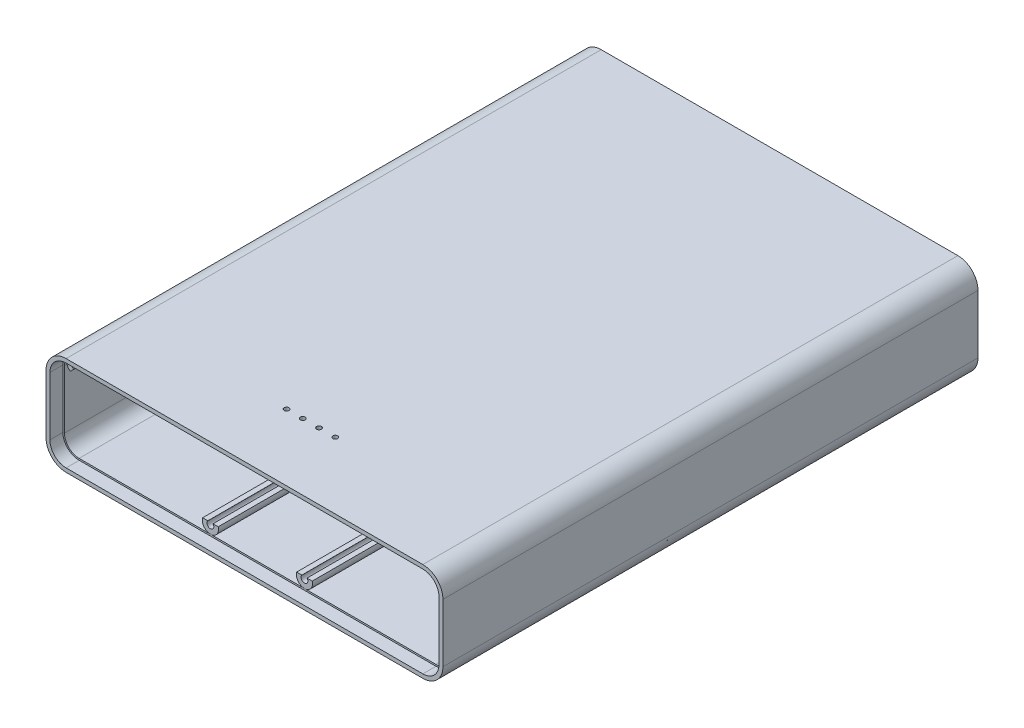
SolidWorks part; units mm, degrees
ref_plane "Front Plane" through (0, 0, 0) normal (0, 0, 1) x (1, 0, 0)
ref_plane "Top Plane" through (0, 0, 0) normal (0, 1, 0) x (1, 0, 0)
ref_plane "Right Plane" through (0, 0, 0) normal (1, 0, 0) x (0, 0, -1)
sketch "Sketch1" plane through (0, 0, 0) normal (0, 0, 1) x (1, 0, 0)
  line L0 (0, 0) -> (0, 26.7771) construction
  line L1 (0, 26.7771) -> (0, -20.8821) construction
  line L2 (0, 14) -> (55, 14)
  line L3 (0, 14) -> (-55, 14)
  line L4 (0, 0) -> (70.3724, 0) construction
  line L5 (73.8857, 0) -> (-73.8857, 0) construction
  line L6 (0, -14) -> (55, -14)
  line L7 (0, -14) -> (-55, -14)
  line L8 (-60, 9) -> (-60, -9)
  line L9 (60, 9) -> (60, -9)
  line L10 (0, 15.2) -> (-55, 15.2)
  line L11 (-61.2, 9) -> (-61.2, -9)
  line L12 (0, -15.2) -> (-55, -15.2)
  line L13 (0, -15.2) -> (55, -15.2)
  line L14 (61.2, 9) -> (61.2, -9)
  line L15 (0, 15.2) -> (55, 15.2)
  line L16 (0, 15.2) -> (-55, 15.2)
  line L17 (-61.2, 9) -> (-61.2, -9)
  line L18 (0, -15.2) -> (-55, -15.2)
  line L19 (0, -15.2) -> (55, -15.2)
  line L20 (61.2, 9) -> (61.2, -9)
  line L21 (0, 15.2) -> (55, 15.2)
  line L22 (-59.5, 9) -> (-59.5, -9)
  line L23 (0, -13.5) -> (-55, -13.5)
  line L24 (0, -13.5) -> (55, -13.5)
  line L25 (59.5, 9) -> (59.5, -9)
  line L26 (0, 13.5) -> (55, 13.5)
  line L27 (0, 13.5) -> (-55, 13.5)
  line L28 (53.8591, 10.8893) -> (57.1976, 8.1517)
  line L29 (-53.8591, 10.8893) -> (-57.1976, 8.1517)
  line L30 (16.7913, -10) -> (12.2087, -10)
  line L31 (-12.2087, -10) -> (-16.7913, -10)
  arc A0 (-55, 15.2) -> (-61.2, 9) centre (-55, 9) ccw
  arc A1 (-55, -15.2) -> (-61.2, -9) centre (-55, -9) cw
  arc A2 (55, -15.2) -> (61.2, -9) centre (55, -9) ccw
  arc A3 (55, 15.2) -> (61.2, 9) centre (55, 9) cw
  arc A4 (-55, 15.2) -> (-61.2, 9) centre (-55, 9) ccw
  arc A5 (-55, -15.2) -> (-61.2, -9) centre (-55, -9) cw
  arc A6 (55, -15.2) -> (61.2, -9) centre (55, -9) ccw
  arc A7 (55, 15.2) -> (61.2, 9) centre (55, 9) cw
  arc A8 (-55, 13.5) -> (-59.5, 9) centre (-55, 9) ccw
  arc A9 (-55, -13.5) -> (-59.5, -9) centre (-55, -9) cw
  arc A10 (55, -13.5) -> (59.5, -9) centre (55, -9) ccw
  arc A11 (55, 13.5) -> (59.5, 9) centre (55, 9) cw
  arc A12 (-53.8591, 10.8893) -> (-57.1976, 8.1517) centre (-56.3279, 10.4955) ccw
  arc A13 (-16.7913, -10) -> (-12.2087, -10) centre (-14.5, -11) ccw
  arc A14 (53.8591, 10.8893) -> (57.1976, 8.1517) centre (56.3279, 10.4955) cw
  arc A15 (16.7913, -10) -> (12.2087, -10) centre (14.5, -11) cw
  arc A16 (55, 14) -> (60, 9) centre (55, 9) cw
  arc A17 (55, -14) -> (60, -9) centre (55, -9) ccw
  arc A18 (-55, -14) -> (-60, -9) centre (-55, -9) cw
  arc A19 (-55, 14) -> (-60, 9) centre (-55, 9) ccw
  point P51 (60, 14)
  point P54 (60, -14)
  point P57 (-60, -14)
  point P60 (-60, 14)
  dimension "D2" = 1.2
  dimension "D3" = 1.2
  dimension "D10" = 0.5
  dimension "D11" = 5
  dimension "D12" = 45
  dimension "D13" = 2.5
  dimension "D14" = 2.5
  dimension "D15" = 2.5
  dimension "D4" = 28
  dimension "D5" = 60
  dimension "D6" = 60
  dimension "D7" = 60
  dimension "D8" = 60
  dimension "D9" = 28
  dimension "D16" = 3.5
  dimension "D17" = 1.2
  dimension "D18" = 0.5
extrude "Boss-Extrude2" add sketch "Sketch1" along normal blind 83 and the other way blind 82 contours A3 L15 L10 A0 L11 A1 L12 L13 A2 L14 A19 L3 L2 A16 L9 A17 L6 L7 A18 L8
sketch "Sketch2" plane through (0, 0, 0) normal (0, 0, 1) x (1, 0, 0)
  line L0 (0, 0.0525) -> (0, 26.8296) construction
  line L1 (0, 26.8296) -> (0, -20.8296) construction
  line L2 (0, 14.0525) -> (55, 14.0525)
  line L3 (0, 14.0525) -> (-55, 14.0525)
  line L4 (0, 0.0525) -> (70.3724, 0.0525) construction
  line L5 (73.8857, 0.0525) -> (-73.8857, 0.0525) construction
  line L6 (0, -13.9475) -> (55, -13.9475)
  line L7 (0, -13.9475) -> (-55, -13.9475)
  line L8 (-60, 9.0525) -> (-60, -8.9475)
  line L9 (60, 9.0525) -> (60, -8.9475)
  line L10 (0, 15.2525) -> (-55, 15.2525)
  line L11 (-61.2, 9.0525) -> (-61.2, -8.9475)
  line L12 (0, -15.1475) -> (-55, -15.1475)
  line L13 (0, -15.1475) -> (55, -15.1475)
  line L14 (61.2, 9.0525) -> (61.2, -8.9475)
  line L15 (0, 15.2525) -> (55, 15.2525)
  line L16 (0, 15.2525) -> (-55, 15.2525)
  line L17 (-61.2, 9.0525) -> (-61.2, -8.9475)
  line L18 (0, -15.1475) -> (-55, -15.1475)
  line L19 (0, -15.1475) -> (55, -15.1475)
  line L20 (61.2, 9.0525) -> (61.2, -8.9475)
  line L21 (0, 15.2525) -> (55, 15.2525)
  line L22 (-59.5, 9.0525) -> (-59.5, -8.9475)
  line L23 (0, -13.4475) -> (-55, -13.4475)
  line L24 (0, -13.4475) -> (55, -13.4475)
  line L25 (59.5, 9.0525) -> (59.5, -8.9475)
  line L26 (0, 13.5525) -> (55, 13.5525)
  line L27 (0, 13.5525) -> (-55, 13.5525)
  line L28 (53.8591, 10.9418) -> (57.1976, 8.2042)
  line L29 (-53.8591, 10.9418) -> (-57.1976, 8.2042)
  line L30 (16.7913, -9.9475) -> (12.2087, -9.9475)
  line L31 (-12.2087, -9.9475) -> (-16.7913, -9.9475)
  arc A0 (-55, 15.2525) -> (-61.2, 9.0525) centre (-55, 9.0525) ccw
  arc A1 (-55, -15.1475) -> (-61.2, -8.9475) centre (-55, -8.9475) cw
  arc A2 (55, -15.1475) -> (61.2, -8.9475) centre (55, -8.9475) ccw
  arc A3 (55, 15.2525) -> (61.2, 9.0525) centre (55, 9.0525) cw
  arc A4 (-55, 15.2525) -> (-61.2, 9.0525) centre (-55, 9.0525) ccw
  arc A5 (-55, -15.1475) -> (-61.2, -8.9475) centre (-55, -8.9475) cw
  arc A6 (55, -15.1475) -> (61.2, -8.9475) centre (55, -8.9475) ccw
  arc A7 (55, 15.2525) -> (61.2, 9.0525) centre (55, 9.0525) cw
  arc A8 (-55, 13.5525) -> (-59.5, 9.0525) centre (-55, 9.0525) ccw
  arc A9 (-55, -13.4475) -> (-59.5, -8.9475) centre (-55, -8.9475) cw
  arc A10 (55, -13.4475) -> (59.5, -8.9475) centre (55, -8.9475) ccw
  arc A11 (55, 13.5525) -> (59.5, 9.0525) centre (55, 9.0525) cw
  arc A12 (-53.8591, 10.9418) -> (-57.1976, 8.2042) centre (-56.3279, 10.548) ccw
  arc A13 (-16.7913, -9.9475) -> (-12.2087, -9.9475) centre (-14.5, -10.9475) ccw
  arc A14 (53.8591, 10.9418) -> (57.1976, 8.2042) centre (56.3279, 10.548) cw
  arc A15 (16.7913, -9.9475) -> (12.2087, -9.9475) centre (14.5, -10.9475) cw
  arc A16 (55, 14.0525) -> (60, 9.0525) centre (55, 9.0525) cw
  arc A17 (55, -13.9475) -> (60, -8.9475) centre (55, -8.9475) ccw
  arc A18 (-55, -13.9475) -> (-60, -8.9475) centre (-55, -8.9475) cw
  arc A19 (-55, 14.0525) -> (-60, 9.0525) centre (-55, 9.0525) ccw
  dimension "D1" = 5
  dimension "D3" = 2.5
  dimension "D4" = 2.5
  dimension "D5" = 2.5
  dimension "D2" = 45
  dimension "D6" = 3.5
extrude "Boss-Extrude3" add sketch "Sketch2" along normal blind 79 and the other way blind 79 contours L3 A19 L8 A18 L7 L6 A17 L9 A16 L2 L26 A11 L25 A10 L24 L23 A9 L22 A8 L27
sketch "Sketch3" plane through (0, 0, 0) normal (0, 0, 1) x (1, 0, 0)
  line L0 (0, 0.0525) -> (0, 26.8296) construction
  line L1 (0, 26.8296) -> (0, -20.8296) construction
  line L2 (0, 14.0525) -> (55, 14.0525)
  line L3 (0, 14.0525) -> (-55, 14.0525)
  line L4 (0, 0.0525) -> (70.3724, 0.0525) construction
  line L5 (73.8857, 0.0525) -> (-73.8857, 0.0525) construction
  line L6 (0, -13.9475) -> (55, -13.9475)
  line L7 (0, -13.9475) -> (-55, -13.9475)
  line L8 (-60, 9.0525) -> (-60, -8.9475)
  line L9 (60, 9.0525) -> (60, -8.9475)
  line L10 (0, 15.2525) -> (-55, 15.2525)
  line L11 (-61.2, 9.0525) -> (-61.2, -8.9475)
  line L12 (0, -15.1475) -> (-55, -15.1475)
  line L13 (0, -15.1475) -> (55, -15.1475)
  line L14 (61.2, 9.0525) -> (61.2, -8.9475)
  line L15 (0, 15.2525) -> (55, 15.2525)
  line L16 (0, 15.2525) -> (-55, 15.2525)
  line L17 (-61.2, 9.0525) -> (-61.2, -8.9475)
  line L18 (0, -15.1475) -> (-55, -15.1475)
  line L19 (0, -15.1475) -> (55, -15.1475)
  line L20 (61.2, 9.0525) -> (61.2, -8.9475)
  line L21 (0, 15.2525) -> (55, 15.2525)
  line L22 (-59.5, 9.0525) -> (-59.5, -8.9475)
  line L23 (0, -13.4475) -> (-55, -13.4475)
  line L24 (0, -13.4475) -> (55, -13.4475)
  line L25 (59.5, 9.0525) -> (59.5, -8.9475)
  line L26 (0, 13.5525) -> (55, 13.5525)
  line L27 (0, 13.5525) -> (-55, 13.5525)
  line L28 (-54.1742, 11.8175) -> (-55.2973, 10.7491)
  line L29 (-16.9055, -10.2666) -> (-15.2993, -10.2666)
  line L30 (-56.5803, 9.5288) -> (-57.7034, 8.4605)
  line L31 (-13.7007, -10.2666) -> (-12.0945, -10.2666)
  line L32 (13.7007, -10.2666) -> (12.0945, -10.2666)
  line L33 (16.9055, -10.2666) -> (15.2993, -10.2666)
  line L34 (56.5803, 9.5288) -> (57.7034, 8.4605)
  line L35 (54.1742, 11.8175) -> (55.2973, 10.7491)
  arc A0 (-55, 15.2525) -> (-61.2, 9.0525) centre (-55, 9.0525) ccw
  arc A1 (-55, -15.1475) -> (-61.2, -8.9475) centre (-55, -8.9475) cw
  arc A2 (55, -15.1475) -> (61.2, -8.9475) centre (55, -8.9475) ccw
  arc A3 (55, 15.2525) -> (61.2, 9.0525) centre (55, 9.0525) cw
  arc A4 (-55, 15.2525) -> (-61.2, 9.0525) centre (-55, 9.0525) ccw
  arc A5 (-55, -15.1475) -> (-61.2, -8.9475) centre (-55, -8.9475) cw
  arc A6 (55, -15.1475) -> (61.2, -8.9475) centre (55, -8.9475) ccw
  arc A7 (55, 15.2525) -> (61.2, 9.0525) centre (55, 9.0525) cw
  arc A8 (-55, 13.5525) -> (-59.5, 9.0525) centre (-55, 9.0525) ccw
  arc A9 (-55, -13.4475) -> (-59.5, -8.9475) centre (-55, -8.9475) cw
  arc A10 (55, -13.4475) -> (59.5, -8.9475) centre (55, -8.9475) ccw
  arc A11 (55, 13.5525) -> (59.5, 9.0525) centre (55, 9.0525) cw
  arc A12 (-54.1742, 11.8175) -> (-57.7034, 8.4605) centre (-56.3279, 10.548) ccw
  arc A13 (-16.9055, -10.2666) -> (-12.0945, -10.2666) centre (-14.5, -10.9475) ccw
  arc A14 (15.2993, -10.2666) -> (13.7007, -10.2666) centre (14.5, -10.9475) cw
  arc A15 (16.9055, -10.2666) -> (12.0945, -10.2666) centre (14.5, -10.9475) cw
  arc A16 (55, 14.0525) -> (60, 9.0525) centre (55, 9.0525) cw
  arc A17 (55, -13.9475) -> (60, -8.9475) centre (55, -8.9475) ccw
  arc A18 (-55, -13.9475) -> (-60, -8.9475) centre (-55, -8.9475) cw
  arc A19 (-55, 14.0525) -> (-60, 9.0525) centre (-55, 9.0525) ccw
  arc A20 (-54.1742, 11.8175) -> (-57.7034, 8.4605) centre (-56.3279, 10.548) ccw
  arc A21 (-16.9055, -10.2666) -> (-12.0945, -10.2666) centre (-14.5, -10.9475) ccw
  arc A22 (16.9055, -10.2666) -> (12.0945, -10.2666) centre (14.5, -10.9475) cw
  arc A23 (55.2973, 10.7491) -> (56.5803, 9.5288) centre (56.3279, 10.548) cw
  arc A24 (-55.2973, 10.7491) -> (-56.5803, 9.5288) centre (-56.3279, 10.548) ccw
  arc A25 (-15.2993, -10.2666) -> (-13.7007, -10.2666) centre (-14.5, -10.9475) ccw
  arc A26 (54.1742, 11.8175) -> (57.7034, 8.4605) centre (56.3279, 10.548) cw
  arc A27 (54.1742, 11.8175) -> (57.7034, 8.4605) centre (56.3279, 10.548) cw
  dimension "D3" = 2.5
  dimension "D5" = 2.5
  dimension "D2" = 45
extrude "Boss-Extrude5" add sketch "Sketch3" along normal blind 79 and the other way blind 79 separate body contours A24 L28 A12 L30 | A25 L29 A13 L31 | A15 L33 A14 L32 | A26 L35 A23 L34
sketch "Sketch9" plane through (0, 0, 0) normal (0, 1, 0) x (1, 0, 0)
  line L0 (-55, -83) -> (55, -83) construction
  line L2 (-61.2, 82) -> (-61.2, -83) construction
  circle A0 centre (-7.5, -62.5) radius 0.75
  circle A1 centre (-2.5, -62.5) radius 0.75
  circle A2 centre (2.5, -62.5) radius 0.75
  circle A3 centre (7.5, -62.5) radius 0.75
  dimension "D1" = 1.5
  dimension "D2" = 20.5
  dimension "D3" = 53.7
  dimension "D4" = 4
extrude "Cut-Extrude3" cut sketch "Sketch9" along normal blind 79
